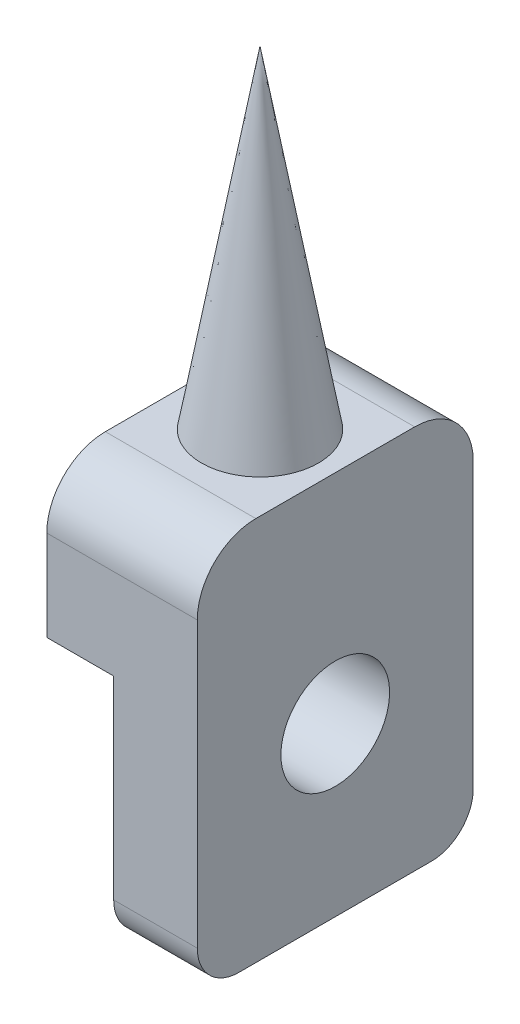
SolidWorks part; units mm, degrees
ref_plane "Front Plane" through (0, 0, 0) normal (0, 0, 1) x (1, 0, 0)
ref_plane "Top Plane" through (0, 0, 0) normal (0, 1, 0) x (1, 0, 0)
ref_plane "Right Plane" through (0, 0, 0) normal (1, 0, 0) x (0, 0, -1)
sketch "Sketch1" plane through (0, 0, 0) normal (0, 1, 0) x (1, 0, 0)
  line L1 (-9, 16.5) -> (9, 16.5)
  line L2 (-9, 16.5) -> (-9, -16.5)
  line L3 (-9, -16.5) -> (9, -16.5)
  line L4 (9, 16.5) -> (9, -16.5)
  line L5 (-9, 16.5) -> (9, -16.5) construction
  line L6 (-9, -16.5) -> (9, 16.5) construction
  point P0 (0, 0)
  dimension "D1" = 33
  dimension "D2" = 18
extrude "Boss-Extrude1" add sketch "Sketch1" along normal blind 46
sketch "Sketch2" plane through (0, 46, 0) normal (0, 1, 0) x (1, 0, 0)
  circle A0 centre (0, 0) radius 7
extrude "Boss-Extrude2" add sketch "Sketch2" along normal blind 40 draft 10
sketch "Sketch3" plane through (-9, 0, 0) normal (-1, 0, 0) x (0, 0, 1)
  line L0 (-16.5, 0) -> (16.5, 0)
  line L1 (-16.5, 0) -> (-16.5, 20)
  line L2 (16.5, 0) -> (16.5, 20)
  arc A0 (16.5, 20) -> (-16.5, 20) centre (0, 20) ccw
  dimension "D1" = 20
  dimension "D2" = 20
extrude "Cut-Extrude1" cut sketch "Sketch3" against normal blind 8
sketch "Sketch4" plane through (-1, 0, 0) normal (-1, 0, 0) x (0, 0, 1)
  circle A0 centre (0, 20) radius 6.5
  dimension "D1" = 13
extrude "Cut-Extrude2" cut sketch "Sketch4" against normal blind 10
fillet "Fillet3" radius 5 2 edges at (4, 0, -16.5) (4, 0, 16.5)
fillet "Fillet4" radius 7 2 edges at (0, 46, -16.5) (0, 46, 16.5)
sketch "Sketch6" plane through (-9, 0, 0) normal (-1, 0, 0) x (0, 0, 1)
  line L0 (-16.5, 20) -> (16.5, 20)
  line L1 (-16.5, 20) -> (-16.5, 28.1854)
  line L2 (-16.5, 39) -> (-16.5, 20) construction
  line L3 (16.5, 20) -> (16.5, 28.1854)
  line L4 (16.5, 39) -> (16.5, 20) construction
  arc A0 (-16.5, 28.1854) -> (16.5, 28.1854) centre (0, 24.0927) cw
extrude "Cut-Extrude3" cut sketch "Sketch6" against normal blind 8
